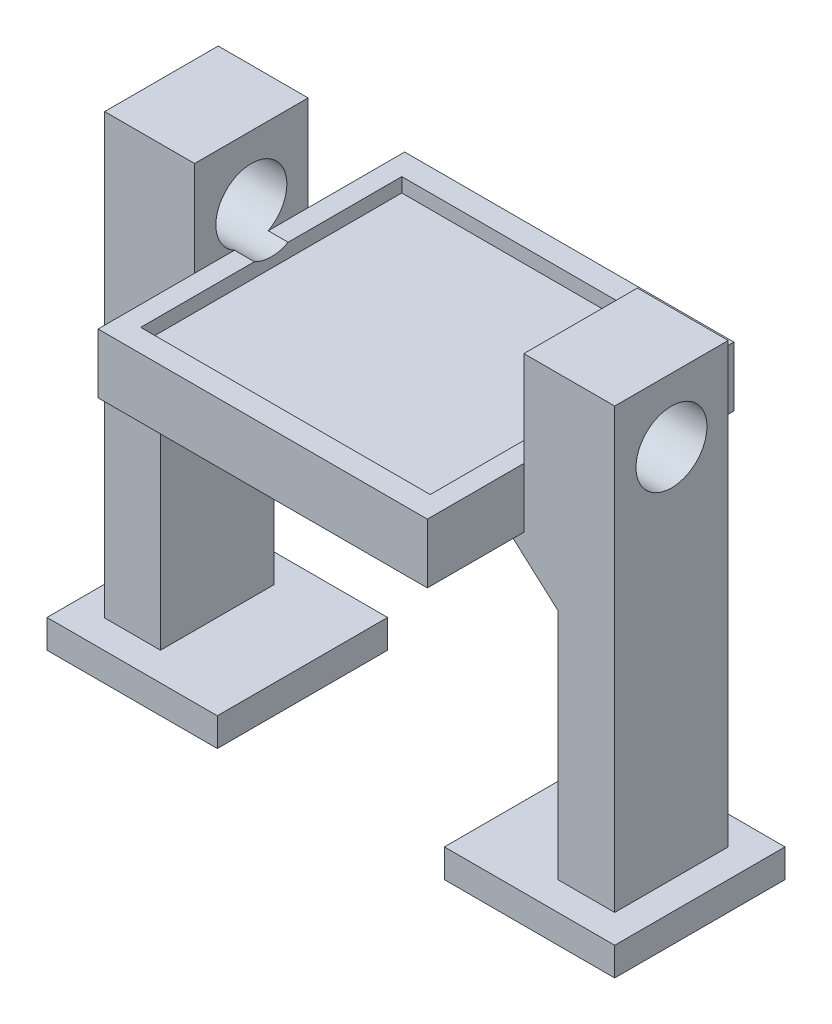
SolidWorks part; units mm, degrees
ref_plane "Front Plane" through (0, 0, 0) normal (0, 0, 1) x (1, 0, 0)
ref_plane "Top Plane" through (0, 0, 0) normal (0, 1, 0) x (1, 0, 0)
ref_plane "Right Plane" through (0, 0, 0) normal (1, 0, 0) x (0, 0, -1)
sketch "Sketch1" plane through (0, 0, 0) normal (0, 1, 0) x (1, 0, 0)
  line L1 (-7.366, 6.858) -> (7.366, 6.858)
  line L2 (-7.366, 6.858) -> (-7.366, -6.858)
  line L3 (-7.366, -6.858) -> (7.366, -6.858)
  line L4 (7.366, 6.858) -> (7.366, -6.858)
  line L5 (-7.366, 6.858) -> (7.366, -6.858) construction
  line L6 (-7.366, -6.858) -> (7.366, 6.858) construction
  point P0 (0, 0)
extrude "Boss-Extrude1" add sketch "Sketch1" along normal blind 2.032
sketch "Sketch6" plane through (0, 0, 0) normal (0, -1, 0) x (-1, 0, 0)
  line L1 (-12.7, 2.54) -> (12.7, 2.54)
  line L2 (-12.7, 2.54) -> (-12.7, -2.54)
  line L3 (-12.7, -2.54) -> (12.7, -2.54)
  line L4 (12.7, 2.54) -> (12.7, -2.54)
  line L5 (-12.7, 2.54) -> (12.7, -2.54) construction
  line L6 (-12.7, -2.54) -> (12.7, 2.54) construction
  point P0 (0, 0)
extrude "Boss-Extrude2" add sketch "Sketch6" along normal blind 12.7
sketch "Sketch15" plane through (0, 0, -2.54) normal (0, 0, -1) x (-1, 0, 0)
  line L0 (-8.89, -12.7) -> (8.89, -12.7)
  line L1 (12.7, -12.7) -> (-12.7, -12.7) construction
  line L2 (6.166, 0) -> (-6.35, 0)
  line L3 (-8.89, -2.27) -> (-6.35, 0)
  line L4 (-11.43, 0) -> (-11.43, -12.7)
  line L6 (-11.43, 0) -> (-12.7, 0)
  line L7 (8.89, -2.27) -> (8.89, -12.7)
  line L8 (-8.89, -2.27) -> (-8.89, -12.7)
  line L10 (12.7, 0) -> (7.366, 0) construction
  line L11 (-6.35, 0) -> (-11.43, 0)
  line L16 (7.366, 0) -> (-7.366, 0) construction
  line L17 (-7.366, 0) -> (-12.7, 0) construction
  line L19 (11.39, 0) -> (11.39, -12.7)
  line L20 (8.89, -2.27) -> (6.166, 0)
  line L21 (-7.366, 0) -> (7.366, 0) construction
  line L22 (11.39, -12.7) -> (12.7, -12.7)
  line L24 (-12.7, 0) -> (-12.7, -12.7)
  line L25 (-12.7, -12.7) -> (-11.43, -12.7)
  line L26 (-11.43, -12.7) -> (-12.7, -12.7)
  line L27 (12.7, -12.7) -> (12.7, 0)
  line L28 (12.7, 0) -> (11.39, 0)
  line M5 (-7.366, 0) -> (-12.7, 0)
  line M6 (-12.7, 0) -> (-12.7, -12.7)
  line M7 (-12.7, -12.7) -> (12.7, -12.7)
  line M8 (12.7, -12.7) -> (12.7, 0)
  line M13 (12.7, 0) -> (7.366, 0)
  line M14 (7.366, 0) -> (-7.366, 0)
sketch "Sketch16" plane through (0, -12.7, 0) normal (0, -1, 0) x (1, 0, 0)
  line L1 (12.7, -3.81) -> (5.08, -3.81)
  line L2 (12.7, -3.81) -> (12.7, 3.81)
  line L3 (12.7, 3.81) -> (5.08, 3.81)
  line L4 (5.08, -3.81) -> (5.08, 3.81)
  line L5 (12.7, -3.81) -> (5.08, 3.81) construction
  line L6 (12.7, 3.81) -> (5.08, -3.81) construction
  line L7 (-12.7, 3.81) -> (-5.08, 3.81)
  line L8 (-12.7, 3.81) -> (-12.7, -3.81)
  line L9 (-12.7, -3.81) -> (-5.08, -3.81)
  line L10 (-5.08, 3.81) -> (-5.08, -3.81)
  line L11 (-12.7, 3.81) -> (-5.08, -3.81) construction
  line L12 (-12.7, -3.81) -> (-5.08, 3.81) construction
  point P0 (8.89, 0)
  point P5 (-8.89, 0)
extrude "Boss-Extrude5" add sketch "Sketch16" along normal blind 1.27
extrude "Cut-Extrude5" cut sketch "Sketch15" against normal blind 10 contours L4 M5 M6 M7 | L7 L20 L3 L8 M14 M7 | L19 M13 M7 M8
sketch "Sketch17" plane through (0, 0, 0) normal (0, 1, 0) x (1, 0, 0)
  line L1 (-11.39, 2.54) -> (-7.366, 2.54)
  line L3 (-7.366, 2.54) -> (-7.366, -2.54)
  line L4 (-11.39, -2.54) -> (-11.39, 2.54)
  line L6 (-7.366, -2.54) -> (-11.39, -2.54)
extrude "Boss-Extrude10" add sketch "Sketch17" along normal blind 6.9215
sketch "Sketch21" plane through (0, 0, 0) normal (0, 1, 0) x (1, 0, 0)
  line L0 (7.366, -6.858) -> (7.366, 6.858) construction
  line L1 (11.43, 2.54) -> (7.366, 2.54)
  line L2 (11.43, -2.54) -> (7.366, -2.54) construction
  line L3 (7.366, -2.54) -> (11.43, -2.54)
  line L4 (11.43, 2.54) -> (11.43, -2.54)
  line L5 (7.366, 2.54) -> (11.43, 2.54) construction
  line L6 (7.366, 2.54) -> (7.366, -2.54)
extrude "Boss-Extrude11" add sketch "Sketch21" along normal blind 6.9215
sketch "Sketch24" plane through (0, 2.032, 0) normal (0, 1, 0) x (1, 0, 0)
  line L1 (-6.477, 5.842) -> (6.477, 5.842)
  line L2 (-6.477, 5.842) -> (-6.477, -5.842)
  line L3 (-6.477, -5.842) -> (6.477, -5.842)
  line L4 (6.477, 5.842) -> (6.477, -5.842)
  line L5 (-6.477, 5.842) -> (6.477, -5.842) construction
  line L6 (-6.477, -5.842) -> (6.477, 5.842) construction
  line L7 (-7.366, 6.858) -> (7.366, 6.858)
  line L8 (-7.366, 6.858) -> (-7.366, -6.858)
  line L9 (-7.366, -6.858) -> (7.366, -6.858)
  line L10 (7.366, 6.858) -> (7.366, -6.858)
  line L11 (-7.366, 6.858) -> (7.366, -6.858) construction
  line L12 (-7.366, -6.858) -> (7.366, 6.858) construction
  point P0 (0, 0)
  point P6 (0, 0)
extrude "Boss-Extrude12" add sketch "Sketch24" along normal blind 0.635
sketch "Sketch23" plane through (-11.39, 0, 0) normal (-1, 0, 0) x (0, 0, 1)
  circle A0 centre (0, 4.064) radius 1.5875
extrude "Cut-Extrude6" cut sketch "Sketch23" against normal blind 25.7175
